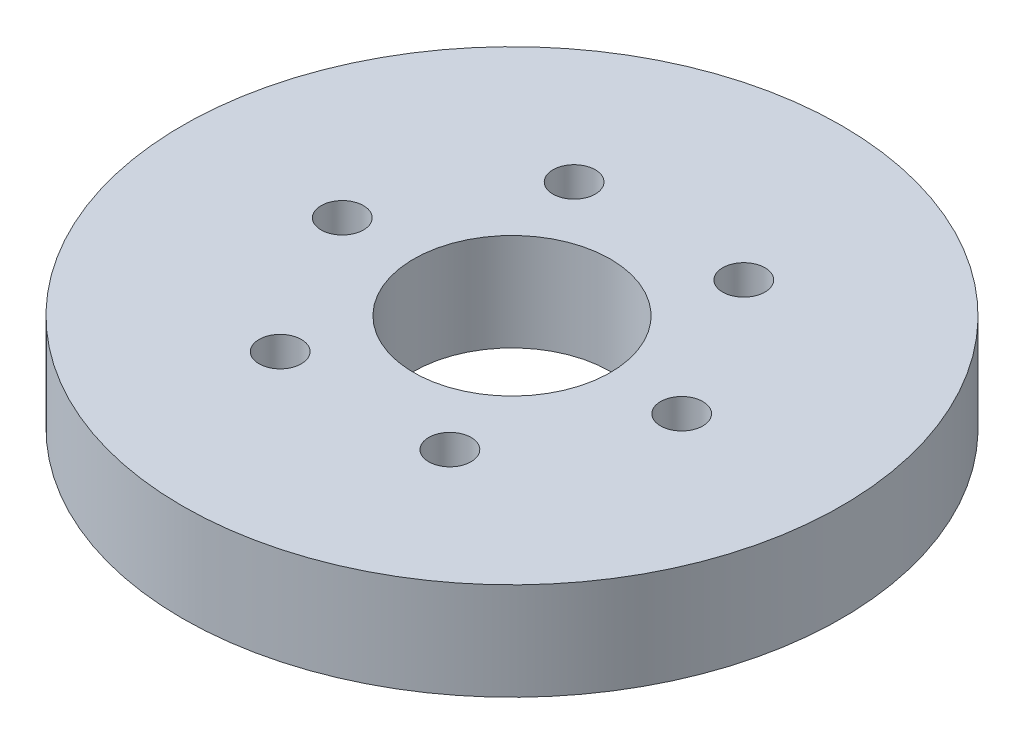
SolidWorks part; units mm, degrees
ref_plane "前视基准面" through (0, 0, 0) normal (0, 0, 1) x (1, 0, 0)
ref_plane "上视基准面" through (0, 0, 0) normal (0, 1, 0) x (1, 0, 0)
ref_plane "右视基准面" through (0, 0, 0) normal (1, 0, 0) x (0, 0, -1)
sketch "草图1" plane through (0, 0, 0) normal (0, 1, 0) x (1, 0, 0)
  line L0 (0, 0) -> (8.625, 14.9389) construction
  line L1 (0, 0) -> (0, 17.25) construction
  circle A0 centre (0, 0) radius 33.5
  circle A2 centre (8.625, 14.9389) radius 2.15
  circle A9 centre (0, 0) radius 10
  circle A10 centre (0, 0) radius 17.25 construction
  circle A11 centre (17.25, 0) radius 2.15
  circle A12 centre (8.625, -14.9389) radius 2.15
  circle A13 centre (-8.625, -14.9389) radius 2.15
  circle A14 centre (-17.25, 0) radius 2.15
  circle A15 centre (-8.625, 14.9389) radius 2.15
  point P30 (0, 0)
  dimension "D1" = 67
  dimension "D2" = 20
  dimension "D4" = 34.5
  dimension "D5" = 4.3
  dimension "D3" = 30
extrude "凸台-拉伸1" add sketch "草图1" along normal blind 9.9
sketch "草图2" plane through (0, 0, 0) normal (0, 1, 0) x (1, 0, 0)
  circle A2 centre (0, 0) radius 27 construction
  arc A4 (3.5355, -30.5355) -> (-3.5355, -30.5355) centre (0, -27) ccw
  circle A6 centre (0, -27) radius 5
  dimension "D1" = 5
  dimension "D2" = 54
extrude "切除-拉伸3" cut sketch "草图2" along normal blind 2.5
sketch "草图5" plane through (0, 0, 0) normal (0, -1, 0) x (1, 0, 0)
  circle A7 centre (0, 0) radius 17.25 construction
  circle A8 centre (-8.625, 14.9389) radius 5
  circle A9 centre (8.625, 14.9389) radius 5
  circle A10 centre (17.25, 0) radius 5
  circle A11 centre (8.625, -14.9389) radius 5
  circle A12 centre (-8.625, -14.9389) radius 5
  circle A13 centre (-17.25, 0) radius 5
  point P22 (0, 0)
  circle M10 centre (8.625, -14.9389) radius 2.15
  circle M22 centre (8.625, 14.9389) radius 2.15
  circle M23 centre (17.25, 0) radius 2.15
  dimension "D1" = 10
extrude "切除-拉伸5" cut sketch "草图5" against normal blind 2 contours A9 M22 | A10 M23 | A11 M10
